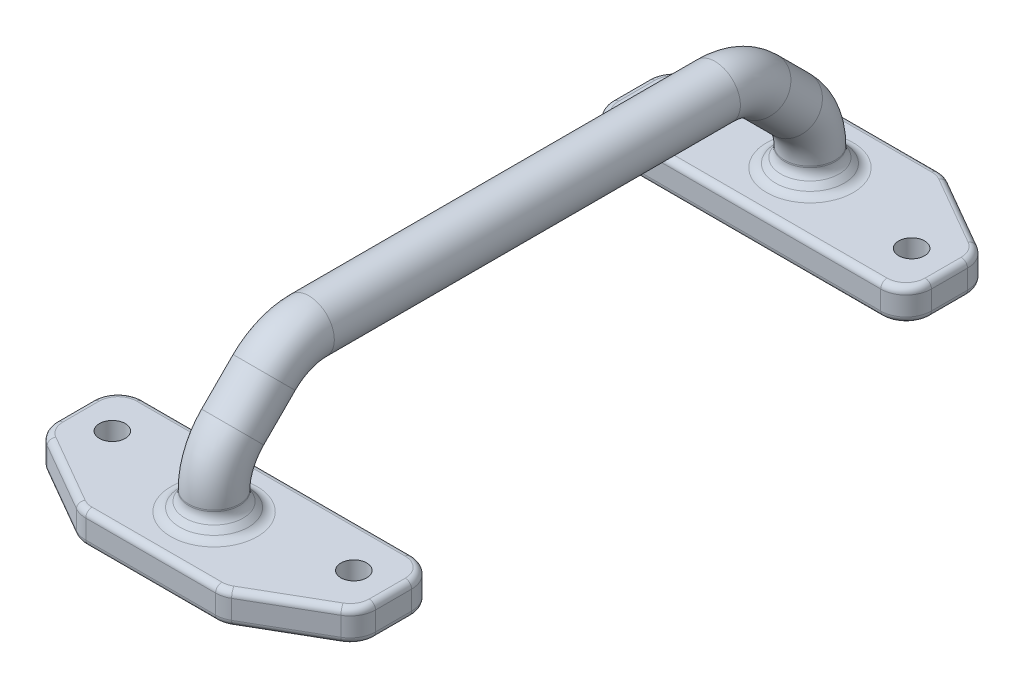
SolidWorks part; units mm, degrees
ref_plane "Front Plane" through (0, 0, 0) normal (0, 0, 1) x (1, 0, 0)
ref_plane "Top Plane" through (0, 0, 0) normal (0, 1, 0) x (1, 0, 0)
ref_plane "Right Plane" through (0, 0, 0) normal (1, 0, 0) x (0, 0, -1)
sketch "Sketch1" plane through (0, 0, 0) normal (0, 1, 0) x (1, 0, 0)
  line L0 (-122.3118, 0) -> (-61.8382, 0)
  line L1 (-132.0273, 11.1125) -> (-52.1227, 11.1125)
  line L2 (-132.0273, 11.1125) -> (-132.0273, -11.1125)
  line L3 (-132.0273, -11.1125) -> (-52.1227, -11.1125)
  line L4 (-52.1227, 11.1125) -> (-52.1227, -11.1125)
  line L5 (-132.0273, 11.1125) -> (-52.1227, -11.1125) construction
  line L6 (-132.0273, -11.1125) -> (-52.1227, 11.1125) construction
  circle A0 centre (-122.3118, 0) radius 3.2385
  circle A1 centre (-61.8382, 0) radius 3.2385
  point P0 (-92.075, 0)
  point P9 (0, 0)
  point P10 (0, 0)
  point P12 (-92.075, 0)
  point P15 (-157.8326, 56.8093)
  dimension "D1" = 6.477
  dimension "D2" = 60.4736
  dimension "D3" = 61.8382
  dimension "D4" = 11.1125
  dimension "D5" = 9.7155
extrude "Boss-Extrude1" add sketch "Sketch1" along normal blind 7.9375
ref_plane "Plane1" through (0, 0, 69.85) normal (0, 0, 1) x (1, 0, 0)
sketch "Sketch6" plane through (0, 0, -11.1125) normal (0, 0, -1) x (-1, 0, 0)
  line L4 (52.1227, 0) -> (132.0273, 0)
  line L5 (132.0273, 0) -> (132.0273, 7.9375)
  line L6 (132.0273, 7.9375) -> (52.1227, 7.9375)
  line L7 (52.1227, 7.9375) -> (52.1227, 0)
  line L8 (52.1227, 0) -> (132.0273, 0)
  line L9 (132.0273, 0) -> (132.0273, 7.9375)
  line L10 (132.0273, 7.9375) -> (52.1227, 7.9375)
  line L11 (52.1227, 7.9375) -> (52.1227, 0)
  dimension "D1" = 0
extrude "Boss-Extrude3" add sketch "Sketch6" along normal blind 9.525
mirror "Mirror3" about plane through (0, 0, 69.85) normal (0, 0, 1) of bodies 105 102
ref_plane "Plane2" through (-92.075, 0, 0) normal (1, 0, 0) x (0, 0, -1)
sketch "Sketch4" plane through (-92.075, 0, 0) normal (1, 0, 0) x (0, 0, -1)
  line L0 (-147.6375, 7.9375) -> (-147.6375, 12.7467)
  line L1 (-160.3375, 7.9375) -> (-128.5875, 7.9375) construction
  line L2 (-142.0579, 26.2171) -> (-134.1671, 34.1079)
  line L3 (-120.6967, 39.6875) -> (-19.0033, 39.6875)
  line L4 (-5.5329, 34.1079) -> (2.3579, 26.2171)
  line L5 (7.9375, 12.7467) -> (7.9375, 7.9375)
  line L6 (20.6375, 7.9375) -> (-11.1125, 7.9375) construction
  line L8 (7.9375, 7.9375) -> (20.6375, 7.9375) construction
  line L10 (-147.6375, 7.9375) -> (-160.3375, 7.9375) construction
  line L11 (-160.3375, 7.9375) -> (-128.5875, 7.9375) construction
  line L12 (20.6375, 7.9375) -> (-11.1125, 7.9375) construction
  arc A1 (2.3579, 26.2171) -> (7.9375, 12.7467) centre (-11.1125, 12.7467) cw
  arc A2 (-19.0033, 39.6875) -> (-5.5329, 34.1079) centre (-19.0033, 20.6375) cw
  arc A3 (-134.1671, 34.1079) -> (-120.6967, 39.6875) centre (-120.6967, 20.6375) cw
  arc A4 (-147.6375, 12.7467) -> (-142.0579, 26.2171) centre (-128.5875, 12.7467) cw
  point P2 (0, 0)
  point P7 (11.9225, 7.9375)
  point P14 (-160.3375, 7.9375)
  point P17 (7.9375, 20.6375)
  point P20 (-11.1125, 39.6875)
  point P31 (-160.3375, 7.9375)
  point P33 (11.1125, 7.9375)
  point P34 (20.6375, 7.9375)
  dimension "D5" = 19.05
  dimension "D1" = 12.7
  dimension "D2" = 19.05
  dimension "D3" = 12.7
sketch "Sketch5" plane through (0, 7.9375, 0) normal (0, 1, 0) x (1, 0, 0)
  line L0 (-92.075, -5.5329) -> (-92.075, 2.3579) construction
  line L1 (-92.075, 7.9375) -> (-92.075, 20.6375) construction
  line L2 (-132.0273, 20.6375) -> (-52.1227, 20.6375) construction
  circle A0 centre (-92.075, 4.7625) radius 6.35
  point P4 (-92.075, 9.3622)
  dimension "D1" = 12.7
  dimension "D2" = 15.875
sweep "Sweep1" add profiles "Sketch5" path "Sketch4"
chamfer "Chamfer1" distance 3.175 angle 45 2 edges at (-92.075, 7.9375, 1.5875) (-92.075, 7.9375, 138.1125)
chamfer "Chamfer2" distance 12.7 angle 60 4 edges at (-52.1227, 3.9688, 160.3375) (-132.0273, 3.9688, 160.3375) (-132.0273, 3.9688, -20.6375) (-52.1227, 3.9688, -20.6375)
fillet "Fillet1" radius 3.175 4 edges at (-92.075, 7.9375, 4.7625) (-92.075, 11.1125, 1.5875) (-92.075, 7.9375, 153.9875) (-92.075, 11.1125, 150.8125)
fillet "Fillet3" radius 6.35 12 edges at (-52.1227, 3.9688, 128.5875) (-132.0273, 3.9688, 128.5875) (-132.0273, 3.9688, 11.1125) (-52.1227, 3.9688, 11.1125) (-132.0273, 3.9688, 147.6375) (-110.0302, 3.9688, 160.3375) (-74.1198, 3.9688, 160.3375) (-52.1227, 3.9688, 147.6375) (-74.1198, 3.9688, -20.6375) (-110.0302, 3.9688, -20.6375) (-132.0273, 3.9688, -7.9375) (-52.1227, 3.9688, -7.9375)
fillet "Fillet4" radius 1.5875 48 edges at (-130.1674, 7.9375, 130.4474) (-132.0273, 7.9375, 139.4544) (-52.1227, 7.9375, 139.4544) (-53.9826, 7.9375, 130.4474) (-132.0273, 7.9375, 0.2456) (-130.1674, 7.9375, 9.2526) (-92.075, 7.9375, 11.1125) (-53.9826, 7.9375, 9.2526) (-92.075, 7.9375, 128.5875) (-52.1227, 7.9375, 0.2456) (-52.1227, 0, 139.4544) (-53.9826, 0, 130.4474) (-92.075, 0, 128.5875) (-130.1674, 0, 130.4474) (-52.1227, 0, 0.2456) (-53.9826, 0, 9.2526) (-92.075, 0, 11.1125) (-130.1674, 0, 9.2526) (-132.0273, 0, 139.4544) (-132.0273, 0, 0.2456) (-92.075, 0, 160.3375) (-92.075, 0, -20.6375) (-92.075, 7.9375, 160.3375) (-92.075, 7.9375, -20.6375) (-131.1766, 0, 147.1463) (-120.178, 0, 154.4787) (-109.9723, 0, 160.1211) (-74.1777, 0, 160.1211) (-63.972, 0, 154.4787) (-52.9734, 0, 147.1463) (-131.1766, 0, -7.4463) (-120.178, 0, -14.7787) (-109.9723, 0, -20.4211) (-74.1777, 0, -20.4211) (-63.972, 0, -14.7787) (-52.9734, 0, -7.4463) (-131.1766, 7.9375, 147.1463) (-120.178, 7.9375, 154.4787) (-109.9723, 7.9375, 160.1211) (-74.1777, 7.9375, 160.1211) (-63.972, 7.9375, 154.4787) (-52.9734, 7.9375, 147.1463) (-52.9734, 7.9375, -7.4463) (-63.972, 7.9375, -14.7787) (-74.1777, 7.9375, -20.4211) (-109.9723, 7.9375, -20.4211) (-120.178, 7.9375, -14.7787) (-131.1766, 7.9375, -7.4463)
